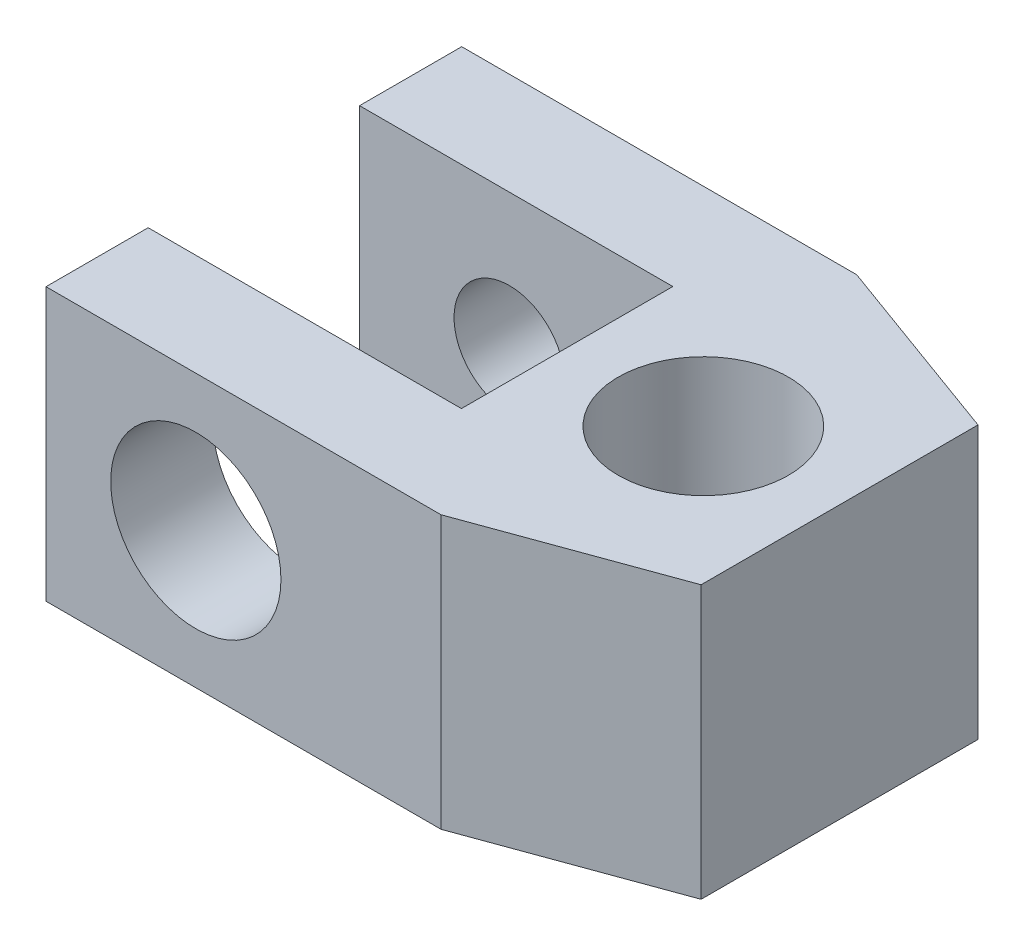
SolidWorks part; units mm, degrees
ref_plane "Front Plane" through (0, 0, 0) normal (0, 0, 1) x (1, 0, 0)
ref_plane "Top Plane" through (0, 0, 0) normal (0, 1, 0) x (1, 0, 0)
ref_plane "Right Plane" through (0, 0, 0) normal (1, 0, 0) x (0, 0, -1)
sketch "Sketch1" plane through (0, 0, 0) normal (0, 1, 0) x (1, 0, 0)
  line L0 (0, 0) -> (27.305, 0)
  line L2 (27.305, 0) -> (27.305, 19.3802)
  line L4 (27.305, 19.3802) -> (0, 19.3802)
  line L5 (0, 19.3802) -> (0, 14.6177)
  line L6 (0, 14.6177) -> (14.605, 14.6177)
  line L7 (14.605, 14.6177) -> (14.605, 4.7625)
  line L8 (14.605, 4.7625) -> (0, 4.7625)
  line L9 (0, 4.7625) -> (0, 0)
  circle A0 centre (20.955, 9.6901) radius 3.9688
  point P15 (14.605, 9.6901)
  dimension "D3" = 7.9375
  dimension "D1" = 9.8552
  dimension "D2" = 14.605
  dimension "D4" = 4.7625
  dimension "D5" = 6.35
  dimension "D6" = 6.35
extrude "Boss-Extrude1" add sketch "Sketch1" along normal blind 12.7
sketch "Sketch2" plane through (0, 0, 0) normal (0, 0, 1) x (1, 0, 0)
  line L0 (0, 6.35) -> (27.305, 6.35) construction
  line L1 (0, 12.7) -> (0, 0) construction
  line L2 (27.305, 12.7) -> (27.305, 0) construction
  line L4 (20.955, 12.7) -> (20.955, 0) construction
  line L5 (0, 12.7) -> (27.305, 12.7) construction
  line L6 (0, 0) -> (27.305, 0) construction
  circle A0 centre (6.985, 6.35) radius 3.9688
  dimension "D2" = 7.9375
  dimension "D1" = 6.35
  dimension "D3" = 13.97
extrude "Cut-Extrude1" cut sketch "Sketch2" against normal up to surface (4.7625 mm away) up to face at (7.3025, 6.35, -4.7625)
sketch "Sketch3" plane through (0, 0, -14.6177) normal (0, 0, 1) x (1, 0, 0)
  circle A0 centre (6.985, 6.35) radius 3.9688 construction
  circle A1 centre (6.985, 6.35) radius 3.9688 construction
  circle A2 centre (6.985, 6.35) radius 2.5797
  dimension "D1" = 5.1594
extrude "Cut-Extrude2" cut sketch "Sketch3" against normal through all
chamfer "Chamfer1" distance 8.89 angle 20 2 edges at (27.305, 6.35, -19.3802) (27.305, 6.35, 0)
